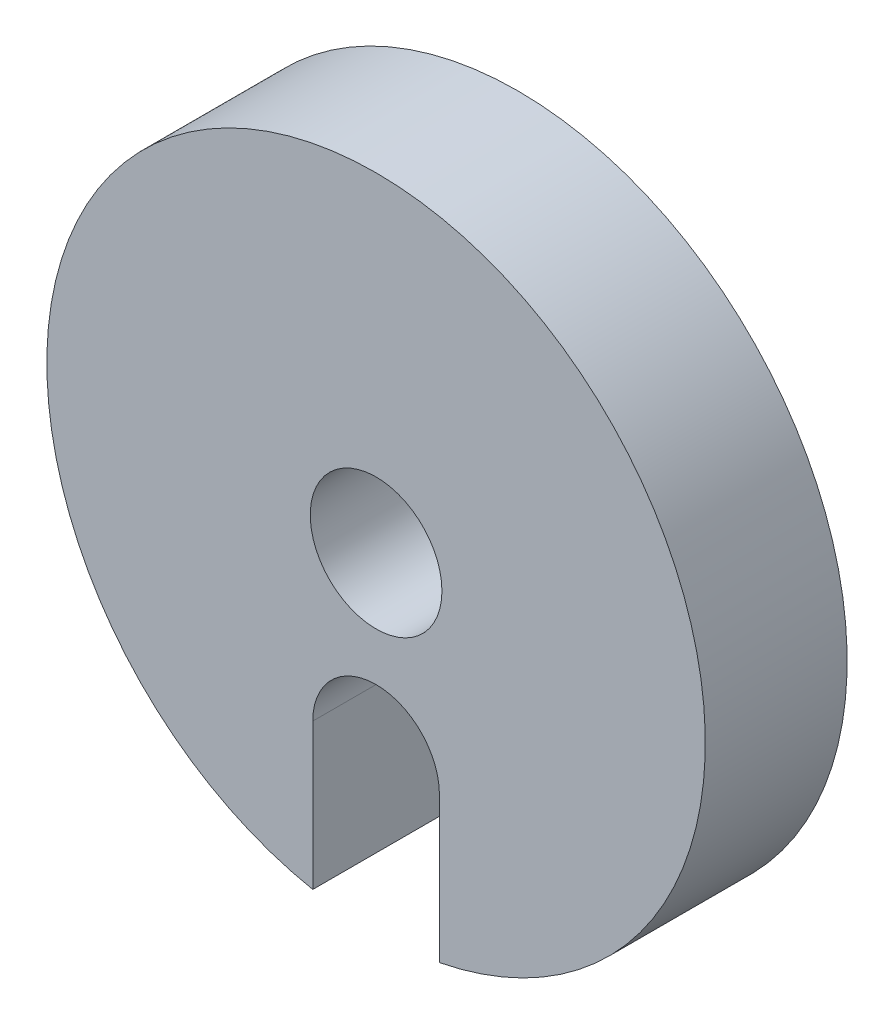
SolidWorks part; units mm, degrees
material "ABS"
ref_plane "Płaszczyzna przednia" through (0, 0, 0) normal (0, 0, 1) x (1, 0, 0)
ref_plane "Płaszczyzna górna" through (0, 0, 0) normal (0, 1, 0) x (1, 0, 0)
ref_plane "Płaszczyzna prawa" through (0, 0, 0) normal (1, 0, 0) x (0, 0, -1)
sketch "Szkic1" plane through (0, 0, 0) normal (0, 0, 1) x (1, 0, 0)
  line L0 (-2.5, -7) -> (-2.5, -12.7574)
  line L1 (2.5, -7) -> (2.5, -12.7574)
  circle A0 centre (0, 0) radius 13
  circle A1 centre (0, 0) radius 2.6
  arc A2 (2.5, -7) -> (-2.5, -7) centre (0, -7) ccw
  dimension "D1" = 26
  dimension "D2" = 5.2
  dimension "D3" = 5
  dimension "D4" = 7
extrude "Dodanie-wyciągnięcie1" add sketch "Szkic1" along normal blind 5.6 contours A2 L1 A0 L0 A1
